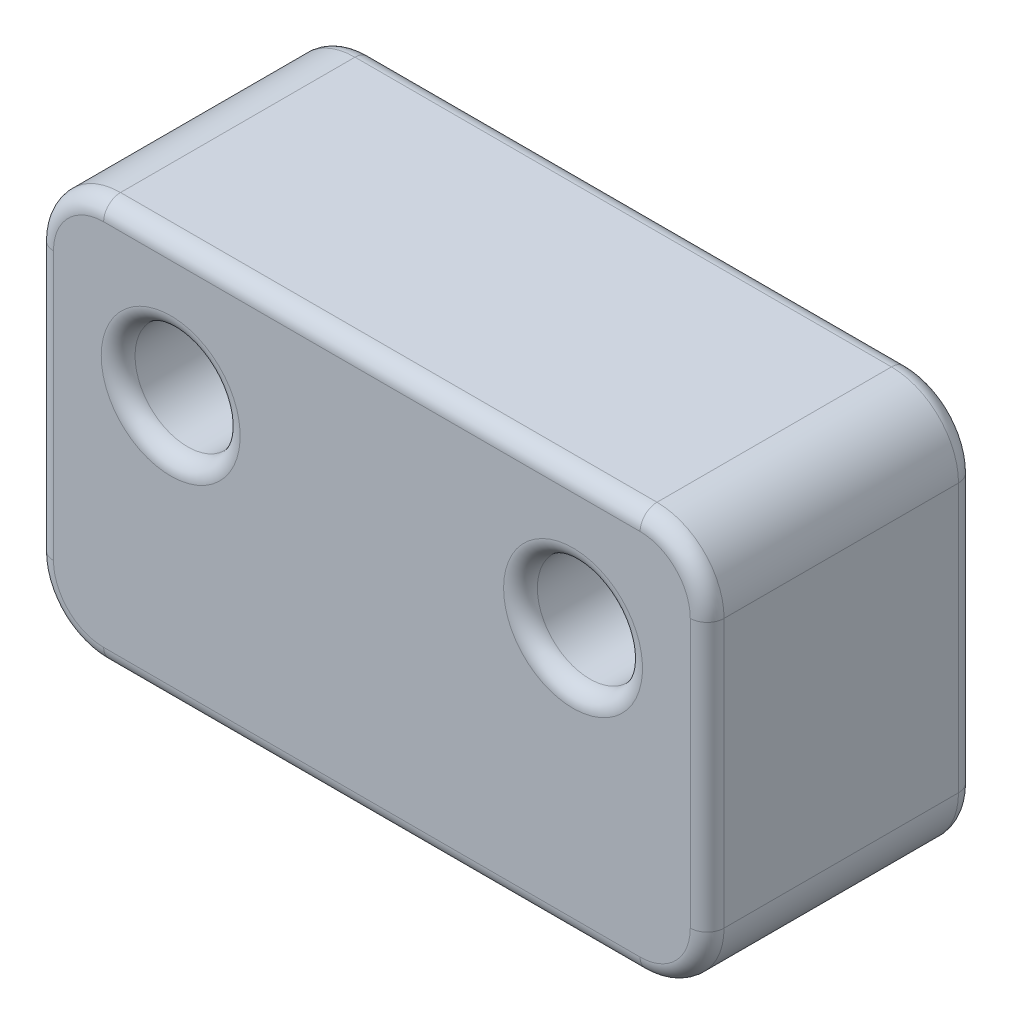
SolidWorks part; units mm, degrees
material "Nylon 101"
ref_plane "Front Plane" through (0, 0, 0) normal (0, 0, 1) x (1, 0, 0)
ref_plane "Top Plane" through (0, 0, 0) normal (0, 1, 0) x (1, 0, 0)
ref_plane "Right Plane" through (0, 0, 0) normal (1, 0, 0) x (0, 0, -1)
sketch "Sketch1" plane through (0, 0, 0) normal (0, 0, 1) x (1, 0, 0)
  line L0 (6.35, 12.7) -> (25.4, 12.7) construction
  line L1 (0, 0) -> (31.75, 0)
  line L2 (0, 0) -> (0, 19.05)
  line L3 (0, 19.05) -> (31.75, 19.05)
  line L4 (31.75, 0) -> (31.75, 19.05)
  circle A0 centre (6.35, 12.7) radius 2.4892
  circle A1 centre (25.4, 12.7) radius 2.4892
  point P10 (15.875, 12.7)
  point P11 (15.875, 19.05)
  dimension "D3" = 4.9784
  dimension "D1" = 31.75
  dimension "D2" = 19.05
  dimension "D4" = 6.35
  dimension "D5" = 19.05
extrude "Boss-Extrude1" add sketch "Sketch1" along normal mid plane 12.7
fillet "Fillet1" radius 3.175 4 edges at (31.75, 19.05, 0) (31.75, 0, 0) (0, 0, 0) (0, 19.05, 0)
fillet "Fillet2" radius 0.8 20 edges at (27.8892, 12.7, -6.35) (27.8892, 12.7, 6.35) (8.8392, 12.7, -6.35) (8.8392, 12.7, 6.35) (15.875, 0, -6.35) (31.75, 9.525, -6.35) (15.875, 19.05, -6.35) (0, 9.525, 6.35) (15.875, 0, 6.35) (31.75, 9.525, 6.35) (0.9299, 18.1201, -6.35) (0.9299, 0.9299, -6.35) (30.8201, 0.9299, -6.35) (30.8201, 18.1201, -6.35) (0.9299, 18.1201, 6.35) (0.9299, 0.9299, 6.35) (30.8201, 0.9299, 6.35) (30.8201, 18.1201, 6.35) (0, 9.525, -6.35) (15.875, 19.05, 6.35)
